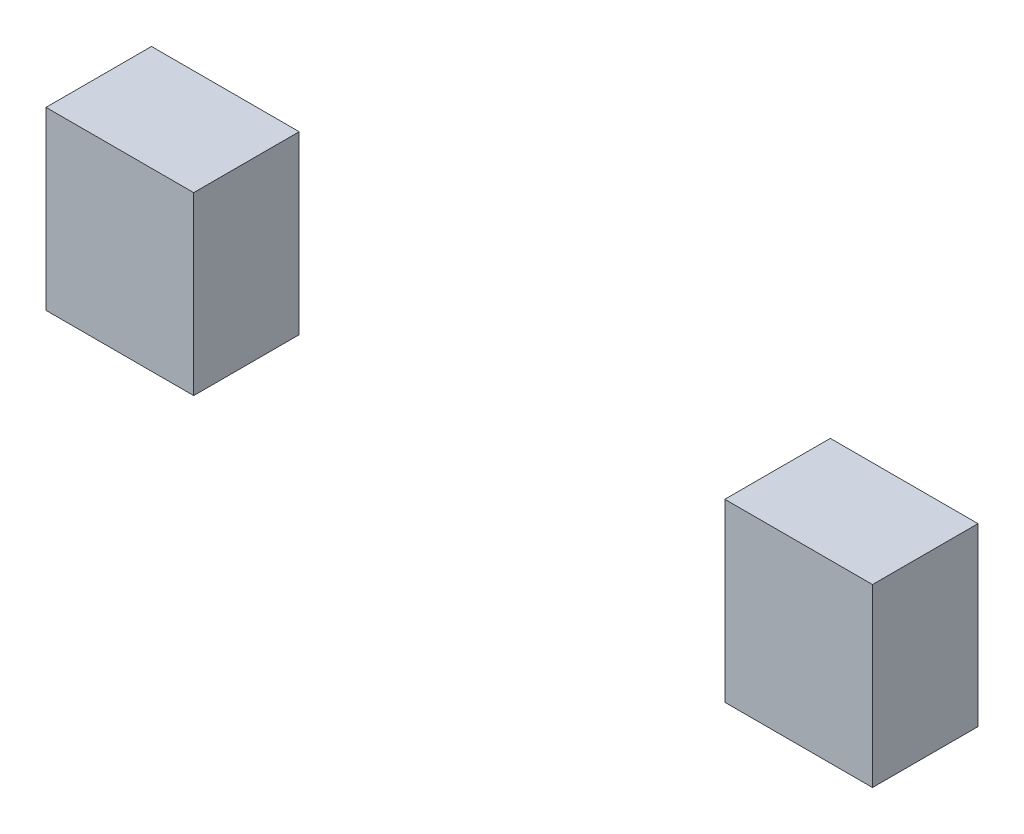
SolidWorks part; units mm, degrees
ref_plane "Front Plane" through (0, 0, 0) normal (0, 0, 1) x (1, 0, 0)
ref_plane "Top Plane" through (0, 0, 0) normal (0, 1, 0) x (1, 0, 0)
ref_plane "Right Plane" through (0, 0, 0) normal (1, 0, 0) x (0, 0, -1)
sketch "QT_connector_1_Profile" plane through (0, 0, 0) normal (0, 0, 1) x (1, 0, 0)
  line L1 (0.748, -2.5) -> (4.948, -2.5)
  line L2 (0.748, -2.5) -> (0.748, 2.5)
  line L3 (0.748, 2.5) -> (4.948, 2.5)
  line L4 (4.948, -2.5) -> (4.948, 2.5)
extrude "QT_connector_1" add sketch "QT_connector_1_Profile" along normal blind 3 from offset 22.55
sketch "QT_connector_2_Profile" plane through (0, 0, 0) normal (0, 0, 1) x (1, 0, 0)
  line L1 (20.052, -2.5) -> (24.252, -2.5)
  line L2 (20.052, -2.5) -> (20.052, 2.5)
  line L3 (20.052, 2.5) -> (24.252, 2.5)
  line L4 (24.252, -2.5) -> (24.252, 2.5)
extrude "QT_connector_2" add sketch "QT_connector_2_Profile" along normal blind 3 from offset 22.55
